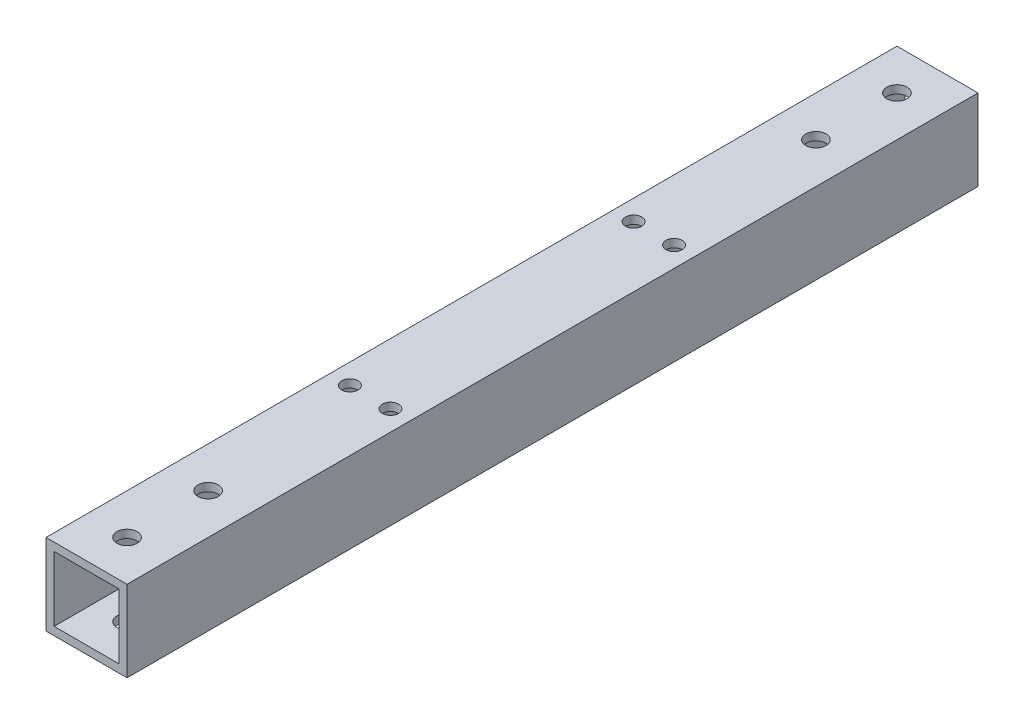
SolidWorks part; units mm, degrees
material "1345 Alloy"
ref_plane "Front Plane" through (0, 0, 0) normal (0, 0, 1) x (1, 0, 0)
ref_plane "Top Plane" through (0, 0, 0) normal (0, 1, 0) x (1, 0, 0)
ref_plane "Right Plane" through (0, 0, 0) normal (1, 0, 0) x (0, 0, -1)
sketch "Sketch1" plane through (0, 0, 0) normal (0, 0, 1) x (1, 0, 0)
  line L1 (-10, 10) -> (10, 10)
  line L2 (-10, 10) -> (-10, -10)
  line L3 (-10, -10) -> (10, -10)
  line L4 (10, 10) -> (10, -10)
  line L5 (-10, 10) -> (10, -10) construction
  line L6 (-10, -10) -> (10, 10) construction
  line L7 (-8, 8) -> (8, 8)
  line L8 (-8, 8) -> (-8, -8)
  line L9 (-8, -8) -> (8, -8)
  line L10 (8, 8) -> (8, -8)
  line L11 (-8, 8) -> (8, -8) construction
  line L12 (-8, -8) -> (8, 8) construction
  point P0 (0, 0)
  point P6 (0, 0)
  dimension "D1" = 20
  dimension "D2" = 20
  dimension "D3" = 16
extrude "Boss-Extrude1" add sketch "Sketch1" along normal blind 210
sketch "Sketch2" plane through (0, 10, 0) normal (0, 1, 0) x (1, 0, 0)
  line L0 (0, 5.0921) -> (0, -216.7902) construction
  line L1 (-10, -105) -> (19.8109, -105) construction
  line L2 (-10, -210) -> (-10, 0) construction
  line L3 (10, 0) -> (-10, 0) construction
  circle A0 centre (0, -10) radius 2.5
  circle A1 centre (0, -30) radius 2.5
  circle A2 centre (0, -200) radius 2.5
  circle A3 centre (0, -180) radius 2.5
  dimension "D1" = 5
  dimension "D2" = 5
  dimension "D3" = 10
  dimension "D4" = 20
extrude "Cut-Extrude1" cut sketch "Sketch2" against normal through all
sketch "Sketch3" plane through (0, 10, 0) normal (0, 1, 0) x (1, 0, 0)
  line L0 (0, 8.4883) -> (0, -217.3562) construction
  line L1 (-22.2637, -105) -> (23.2071, -105) construction
  line L2 (10, 0) -> (-10, 0) construction
  line L3 (-22.2637, -70) -> (23.2071, -70) construction
  circle A0 centre (-5, -70) radius 2
  circle A1 centre (5, -70) radius 2
  circle A2 centre (5, -140) radius 2
  circle A3 centre (-5, -140) radius 2
  dimension "D3" = 4
  dimension "D1" = 105
  dimension "D2" = 35
  dimension "D4" = 5
extrude "Cut-Extrude2" cut sketch "Sketch3" against normal through all
